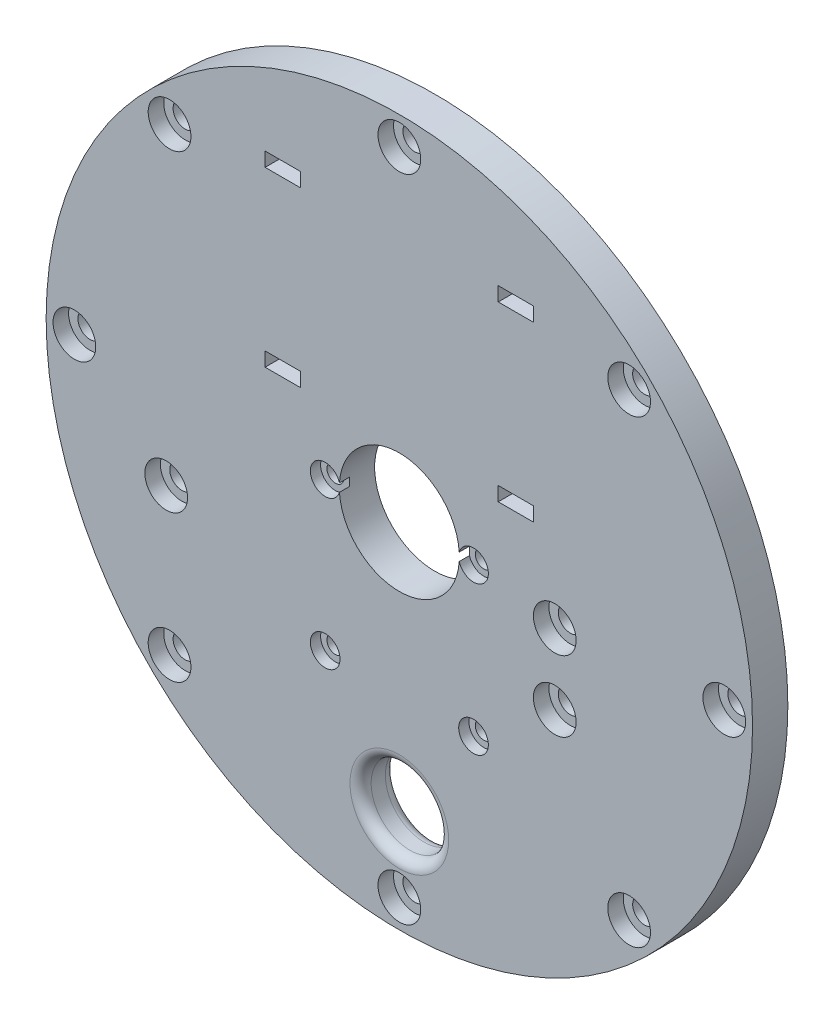
SolidWorks part; units mm, degrees
ref_plane "正面" through (0, 0, 0) normal (0, 0, 1) x (1, 0, 0)
ref_plane "平面" through (0, 0, 0) normal (0, 1, 0) x (1, 0, 0)
ref_plane "右側面" through (0, 0, 0) normal (1, 0, 0) x (0, 0, -1)
sketch "ｽｹｯﾁ1" plane through (0, 0, 0) normal (0, 0, 1) x (1, 0, 0)
  circle A0 centre (0, 0) radius 50
  dimension "D1" = 100
extrude "ﾎﾞｽ - 押し出し1" add sketch "ｽｹｯﾁ1" along normal blind 5
hole_wizard "M2 丸平ねじ用座ぐり穴1" positions "ｽｹｯﾁ2" profile "ｽｹｯﾁ3" counterbore size "M2" standard "JIS" end condition through all
sketch "ｽｹｯﾁ2" plane through (0, 0, 5) normal (0, 0, 1) x (1, 0, 0)
  point P0 (-10.5, 0)
  point P4 (-10.5, -21)
  dimension "D1" = 10.5
  dimension "D2" = 10.5
  dimension "D3" = 21
sketch "ｽｹｯﾁ3" plane through (-10.5, 0, 5) normal (1, 0, 0) x (0, -1, 0)
  line L0 (0, 0) -> (0, 5)
  line L1 (0, 5) -> (1.2, 5)
  line L3 (1.2, 5) -> (1.2, 1.45)
  line L4 (1.2, 1.45) -> (2.1, 1.45)
  line L5 (2.1, 1.45) -> (2.1, 0)
  line L7 (2.1, 0) -> (0, 0)
  line L11 (0, -6.35) -> (0, 107.95) construction
  dimension "通し穴の直径" = 2.4
  dimension "通し穴の深さ" = 5
  dimension "座ぐり穴の直径" = 4.2
  dimension "座ぐり穴の深さ" = 1.45
mirror "ﾐﾗｰ1" about plane through (0, 0, 0) normal (1, 0, 0) of "M2 丸平ねじ用座ぐり穴1"
hole_wizard "M3 丸平ねじ用座ぐり穴2" positions "ｽｹｯﾁ4" profile "ｽｹｯﾁ5" counterbore size "M3" standard "JIS" end condition through all
sketch "ｽｹｯﾁ4" plane through (0, 0, 5) normal (0, 0, 1) x (1, 0, 0)
  point P0 (46, 0)
  point P2 (46, 0)
  dimension "D1" = 46
sketch "ｽｹｯﾁ5" plane through (46, 0, 5) normal (1, 0, 0) x (0, -1, 0)
  line L0 (0, 0) -> (0, 5)
  line L1 (0, 5) -> (1.7, 5)
  line L3 (1.7, 5) -> (1.7, 2.2)
  line L4 (1.7, 2.2) -> (3.025, 2.2)
  line L5 (3.025, 2.2) -> (3.025, 0)
  line L7 (3.025, 0) -> (0, 0)
  line L11 (0, -6.35) -> (0, 107.95) construction
  dimension "通し穴の直径" = 3.4
  dimension "通し穴の深さ" = 5
  dimension "座ぐり穴の直径" = 6.05
  dimension "座ぐり穴の深さ" = 2.2
pattern_circular "円形ﾊﾟﾀｰﾝ1" count 8 every 45 about axis through (0, 0, 0) along (0, 0, 1) of "M3 丸平ねじ用座ぐり穴2"
sketch "ｽｹｯﾁ6" plane through (0, 0, 5) normal (0, 0, 1) x (1, 0, 0)
  circle A0 centre (0, 0) radius 8.5
  dimension "D1" = 17
extrude "ｶｯﾄ - 押し出し1" cut sketch "ｽｹｯﾁ6" against normal through all
sketch "ｽｹｯﾁ7" plane through (0, 0, 5) normal (0, 0, 1) x (1, 0, 0)
  line L0 (0, -40.975) -> (0, -42.975) construction
  line L1 (0, 0) -> (0, -30) construction
  circle A0 centre (0, -35.4875) radius 5.4875
  circle A1 centre (0, -46) radius 3.025 construction
  dimension "D1" = 30
  dimension "D2" = 2
extrude "ｶｯﾄ - 押し出し2" cut sketch "ｽｹｯﾁ7" against normal through all
fillet "ﾌｨﾚｯﾄ1" radius 1.5 2 edges at (5.4875, -35.4875, 5) (5.4875, -35.4875, 0)
hole_wizard "M3 丸平ねじ用座ぐり穴3" positions "ｽｹｯﾁ9" profile "ｽｹｯﾁ10" counterbore size "M3" standard "JIS" end condition through all
sketch "ｽｹｯﾁ9" plane through (0, 0, 5) normal (0, 0, 1) x (1, 0, 0)
  point P0 (22, -2)
  point P4 (22, -12)
  point P5 (-33, -12)
  dimension "D1" = 22
  dimension "D2" = 2
  dimension "D3" = 10
  dimension "D4" = 33
  dimension "D5" = 12
sketch "ｽｹｯﾁ10" plane through (22, -2, 5) normal (1, 0, 0) x (0, -1, 0)
  line L0 (0, 0) -> (0, 5)
  line L1 (0, 5) -> (1.7, 5)
  line L3 (1.7, 5) -> (1.7, 2.2)
  line L4 (1.7, 2.2) -> (3.025, 2.2)
  line L5 (3.025, 2.2) -> (3.025, 0)
  line L7 (3.025, 0) -> (0, 0)
  line L11 (0, -6.35) -> (0, 107.95) construction
  dimension "通し穴の直径" = 3.4
  dimension "通し穴の深さ" = 5
  dimension "座ぐり穴の直径" = 6.05
  dimension "座ぐり穴の深さ" = 2.2
sketch "ｽｹｯﾁ11" plane through (0, 0, 0) normal (0, 0, -1) x (-1, 0, 0)
  line L1 (-24, 11.5) -> (24, 11.5)
  line L2 (-24, 11.5) -> (-24, 34)
  line L3 (-24, 34) -> (24, 34)
  line L4 (24, 11.5) -> (24, 34)
  point P4 (0, 11.5)
  dimension "D1" = 11.5
  dimension "D2" = 48
  dimension "D3" = 22.5
sketch "ｽｹｯﾁ12" plane through (0, 0, 0) normal (0, 0, -1) x (-1, 0, 0)
  line L0 (-24, 34) -> (24, 34) construction
  line L11 (-24, 11.5) -> (24, 11.5) construction
  line L12 (19, 36) -> (14, 36)
  line L13 (19, 36) -> (19, 34)
  line L14 (19, 34) -> (14, 34)
  line L15 (14, 36) -> (14, 34)
  line L16 (19, 11.5) -> (14, 11.5)
  line L17 (19, 11.5) -> (19, 9.5)
  line L18 (19, 9.5) -> (14, 9.5)
  line L19 (14, 11.5) -> (14, 9.5)
  line L20 (24, 11.5) -> (24, 34) construction
  dimension "D4" = 5
  dimension "D5" = 2
  dimension "D6" = 5
extrude "ｶｯﾄ - 押し出し4" cut sketch "ｽｹｯﾁ12" against normal through all
sketch "ｽｹｯﾁ14" plane through (0, 0, 0) normal (0, 0, -1) x (-1, 0, 0)
  line L11 (24, 11.5) -> (24, 34) construction
  line L12 (24, 32) -> (26, 32)
  line L13 (24, 32) -> (24, 27)
  line L14 (24, 27) -> (26, 27)
  line L15 (26, 32) -> (26, 27)
  line L16 (26, 27) -> (26, 18.5) construction
  line L17 (24, 18.5) -> (26, 18.5)
  line L18 (24, 18.5) -> (24, 13.5)
  line L19 (24, 13.5) -> (26, 13.5)
  line L20 (26, 18.5) -> (26, 13.5)
  line L21 (-24, 34) -> (24, 34) construction
  point P0 (24, 22.75)
  point P1 (26, 22.75)
  dimension "D1" = 2
  dimension "D2" = 5
  dimension "D3" = 2
extrude "ﾎﾞｽ - 押し出し2" add sketch "ｽｹｯﾁ14" along normal blind 3
fillet "ﾌｨﾚｯﾄ2" radius 1 2 edges at (-26, 16, 0) (-26, 29.5, 0)
mirror "ﾐﾗｰ2" about plane through (0, 0, 0) normal (1, 0, 0) of "ｶｯﾄ - 押し出し4", "ﾌｨﾚｯﾄ2", "ﾎﾞｽ - 押し出し2"
